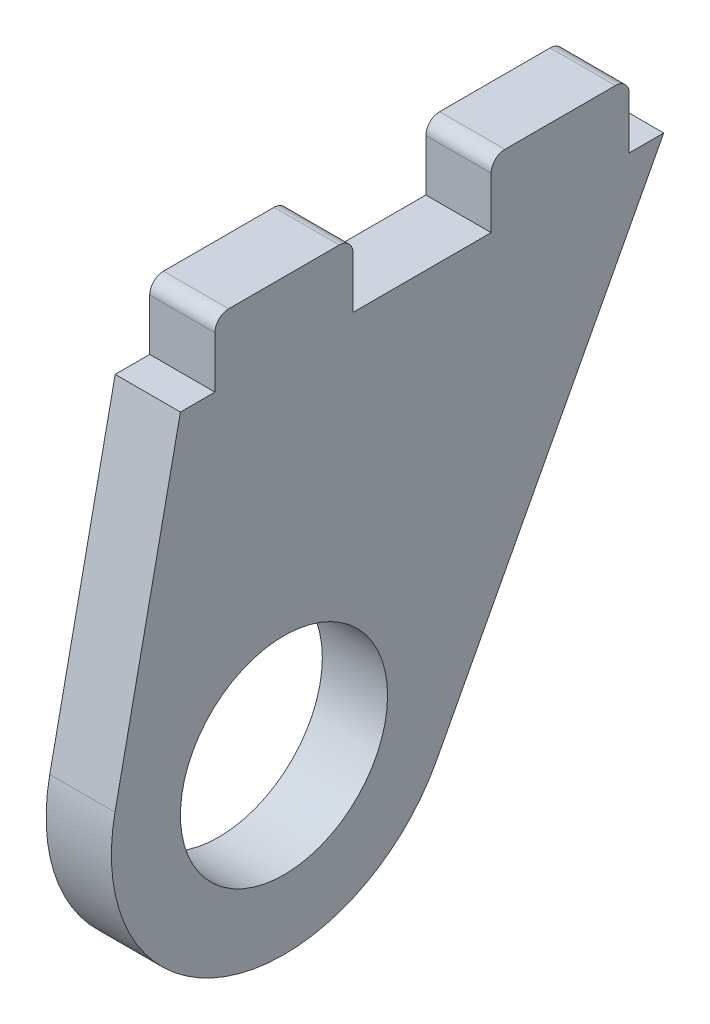
SolidWorks part; units mm, degrees
ref_plane "Front Plane" through (0, 0, 0) normal (0, 0, 1) x (1, 0, 0)
ref_plane "Top Plane" through (0, 0, 0) normal (0, 1, 0) x (1, 0, 0)
ref_plane "Right Plane" through (0, 0, 0) normal (1, 0, 0) x (0, 0, -1)
sketch "Sketch1" plane through (0, 0, 0) normal (1, 0, 0) x (0, 0, -1)
  line L0 (-41.4563, 38.1) -> (38.3452, 38.1) construction
  line L1 (-15.541, 3.2395) -> (-9.525, 32.1)
  line L2 (38.9021, 32.1) -> (-38.9021, 32.1) construction
  line L3 (38.9021, 32.1) -> (38.9021, 38.1) construction
  line L4 (38.9021, 38.1) -> (-38.9021, 38.1) construction
  line L5 (-38.9021, 32.1) -> (-38.9021, 38.1) construction
  line L6 (38.9021, 32.1) -> (-38.9021, 38.1) construction
  line L7 (38.9021, 38.1) -> (-38.9021, 32.1) construction
  line L8 (0, 7.3323) -> (-6.35, 3.6662) construction
  line L9 (-6.35, 3.6662) -> (-6.35, -3.6662) construction
  line L10 (-6.35, -3.6662) -> (0, -7.3323) construction
  line L11 (0, -7.3323) -> (6.35, -3.6662) construction
  line L12 (6.35, -3.6662) -> (6.35, 3.6662) construction
  line L13 (6.35, 3.6662) -> (0, 7.3323) construction
  line L14 (-9.525, 32.1) -> (34.925, 32.1)
  line L15 (14.0348, -7.419) -> (34.925, 32.1)
  circle A0 centre (0, 0) radius 9.525
  arc A1 (-15.541, 3.2395) -> (14.0348, -7.419) centre (0, 0) ccw
  circle A2 centre (0, 0) radius 25.4 construction
  circle A3 centre (0, 0) radius 6.35 construction
  arc A4 (14.0348, -7.419) -> (-15.541, 3.2395) centre (0, 0) ccw construction
  point P3 (60.325, 32.5726)
  point P7 (0, 35.1)
  point P23 (29.7027, 32.1)
  dimension "D1" = 19.05
  dimension "D2" = 6.35
  dimension "D4" = 50.8
  dimension "D3" = 38.1
  dimension "D5" = 6
  dimension "D6" = 12.7
  dimension "D7" = 9.525
  dimension "D8" = 44.45
extrude "Boss-Extrude1" add sketch "Sketch1" along normal mid plane 6
sketch "Sketch3" plane through (0, 32.1, 0) normal (0, 1, 0) x (1, 0, 0)
  line L0 (3, 34.925) -> (3, -9.525) construction
  line L1 (-3, -6.35) -> (3, -6.35)
  line L2 (-3, -6.35) -> (-3, 6.35)
  line L3 (-3, 6.35) -> (3, 6.35)
  line L4 (3, -6.35) -> (3, 6.35)
  line L5 (-3, -6.35) -> (3, 6.35) construction
  line L6 (-3, 6.35) -> (3, -6.35) construction
  point P0 (0, 0)
  dimension "D1" = 12.7
extrude "Boss-Extrude2" add sketch "Sketch3" along normal blind 6
fillet "Fillet1" radius 1.27 2 edges at (0, 38.1, -6.35) (0, 38.1, 6.35)
pattern_linear "LPattern1" count 2 spacing 25.4 along (0, 0, -1) of "Boss-Extrude2", "Fillet1"
